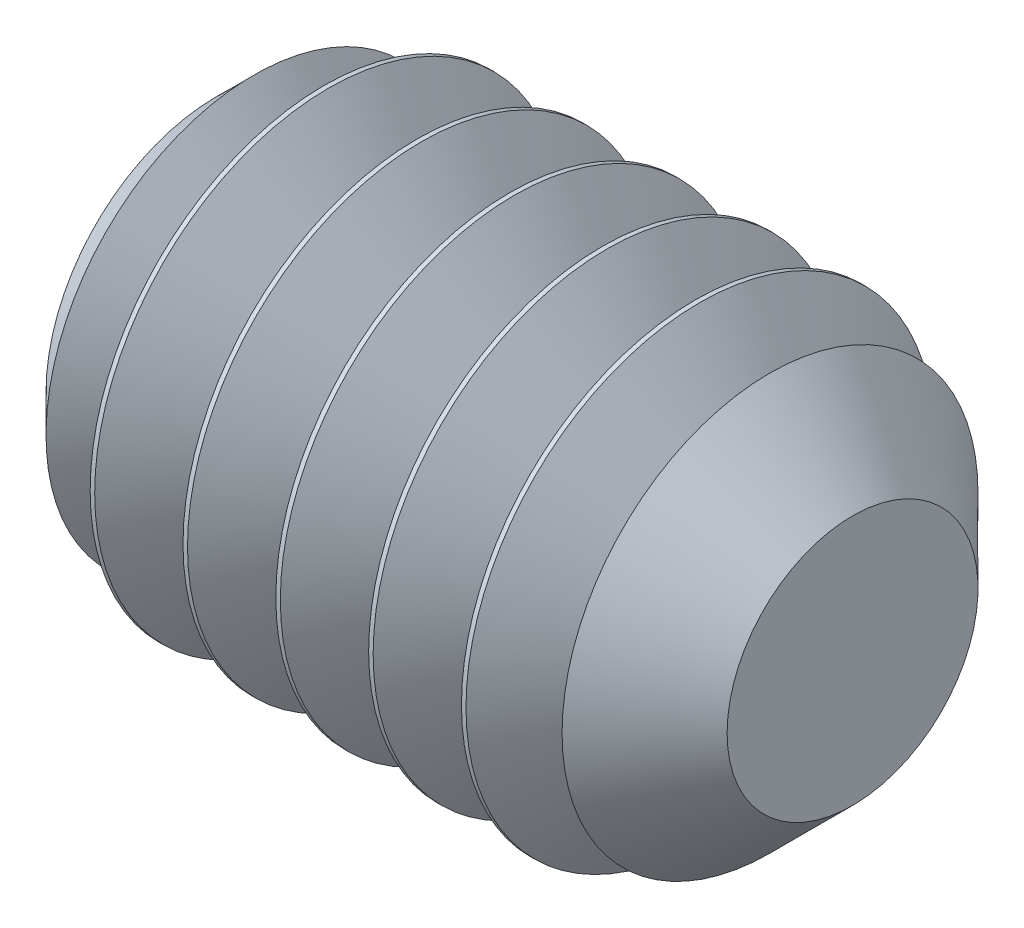
SolidWorks part; units mm, degrees
revolve "BaseBody" add sketch "BodySke" angle 360 about L5
sketch "BodySke" plane through (0, 0, 0) normal (0, 0, 1) x (1, 0, 0)
  line L0 (0, 0) -> (0, 1.2802)
  line L1 (0, 1.2802) -> (0.4724, 1.7526)
  line L2 (0.4724, 1.7526) -> (3.9497, 1.7526)
  line L3 (3.9497, 1.7526) -> (4.7625, 0.9398)
  line L4 (4.7625, 0) -> (0, 0)
  line L5 (-12.7, 0) -> (88.9, 0) construction
  line L6 (4.7625, 0.9398) -> (4.7625, 0)
  line L7 (4.7625, 0.9398) -> (4.7625, 10.4648) construction
  line L8 (0, -1.2802) -> (0.4724, -1.7526) construction
  line L9 (0.7925, 15.875) -> (0.7925, -3.175) construction
  line L10 (3.9497, -1.7526) -> (4.7625, -0.9398) construction
  dimension "Diameter" = 3.5052
  dimension "Drive_ch_ang" = 45
  dimension "Minor_dia" = 2.5603
  dimension "Cup_nose_ang" = 45
  dimension "Cup_dia" = 1.8796
  dimension "Length" = 4.7625
  dimension "Advance" = 0.7925
cosmetic thread "ThreadCosmetic" [suppressed] parameters "Thread_minor"=2.5603
ref_plane "Plane1" through (0, 0, 0) normal (0, 0, 1) x (1, 0, 0)
ref_plane "Plane2" through (0, 0, 0) normal (0, 1, 0) x (1, 0, 0)
ref_plane "Plane3" through (0, 0, 0) normal (1, 0, 0) x (0, 0, -1)
sketch "Sketch2" plane through (0, 0, 0) normal (-1, 0, 0) x (0, 0, 1)
  line L0 (0.4583, 0.7938) -> (-0.4583, 0.7938)
  line L1 (-0.4583, 0.7938) -> (-0.9165, 0)
  line L2 (0.4583, 0.7938) -> (0.9165, 0)
  line L3 (0.4583, -0.7937) -> (0.9165, 0)
  line L4 (0.4583, -0.7937) -> (-0.4583, -0.7937)
  line L5 (-0.4583, -0.7937) -> (-0.9165, 0)
  dimension "Hex_size" = 1.5875
  dimension "D2" = 0.7937
  dimension "D3" = 0.7937
extrude "Hex" cut sketch "Sketch2" against normal blind 2.032
sketch "Sketch4" plane through (0, 4.7709, -0.5249) normal (-1, 0, 0) x (0, 0, 1)
  line L0 (0.5249, -4.7709) -> (1.4647, -4.7709)
  line L1 (0.5249, -4.7709) -> (6.6732, -1.2211) construction
  line L2 (0.5249, -4.7709) -> (0.9948, -3.957)
  line L3 (1.308, -4.5534) -> (1.4211, -4.4881)
  line L4 (1.1048, -4.2014) -> (1.2179, -4.1361)
  arc A0 (1.308, -4.5534) -> (1.1048, -4.2014) centre (0.5249, -4.7709) ccw
  arc A1 (1.4647, -4.7709) -> (1.4211, -4.4881) centre (0.5249, -4.7709) ccw
  arc A2 (0.9948, -3.957) -> (1.2179, -4.1361) centre (0.5249, -4.7709) cw
  circle A3 centre (0.5249, -4.7709) radius 0.8128 construction
  circle A4 centre (0.5249, -4.7709) radius 0.9398 construction
  dimension "Spline_n_dim" = 1.6256
  dimension "Spline_m_dim" = 1.8796
  dimension "D1" = 30
  dimension "Spline_a_dim" = 60
  dimension "Spline_p_dim" = 0.4064
  dimension "D3" = 0.2032
extrude "Spline" [suppressed] cut sketch "Sketch4" against normal blind 1.397
pattern_circular "CirPattern1" [suppressed] count 6 every 60 about axis through (-12.7, 0, 0) along (1, 0, 0)
sketch "ThdSchSke" plane through (0, 0, 0) normal (0, 0, 1) x (1, 0, 0)
  line L0 (0.4724, -1.2802) -> (0.1416, -1.7526)
  line L1 (0.4724, -1.2802) -> (0.8032, -1.7526)
  line L2 (0.8032, -1.7526) -> (0.8032, -2.1907)
  line L3 (-3.175, 0) -> (5.1513, 0) construction
  line L4 (0.4724, 1.7526) -> (0.4724, -1.7526) construction
  line L5 (0.8032, -2.1907) -> (0.1416, -2.1907)
  line L6 (0.1416, -2.1907) -> (0.1416, -1.7526)
  dimension "Thread_minor" = 2.5603
  dimension "Diameter" = 3.5052
revolve "ThreadSchematic" cut sketch "ThdSchSke" angle 360 about L3
pattern_linear "ThdSchPat" count 6 spacing 0.6955 along (1, 0, 0) of "ThreadSchematic"
equation "\"D2@Sketch2\" = \"Hex_size@Sketch2\" / 2"
equation "\"D3@Sketch2\" = \"Hex_size@Sketch2\" / 2"
equation "\"Thread_minor@ThreadCosmetic\" = \"Minor_dia@BodySke\""
equation "\"D1@Sketch4\" = \"Spline_a_dim@Sketch4\" / 2"
equation "\"D3@Sketch4\" = \"Spline_p_dim@Sketch4\" / 2"
equation "\"D2@CirPattern1\" = \"Spline_a_dim@Sketch4\""
equation "\"Num_teeth@CirPattern1\" = 360 / \"D2@CirPattern1\""
equation "\"Thread_minor@ThdSchSke\" = \"Thread_minor@ThreadCosmetic\""
equation "\"Diameter@ThdSchSke\" = \"Diameter@BodySke\""
equation "\"Overcut@ThdSchSke\" = \"Diameter@BodySke\" * 1.25"
equation "\"Num_threads@ThdSchPat\" = int( (\"Length@BodySke\" - ( ( ( \"Diameter@BodySke\" - \"Minor_dia@BodySke\" ) * 0.5 ) / tan( \"Drive_ch_ang@BodySke\" * 0.017453292 ) ) - ( ( ( \"Diameter@BodySke\" - \"Cup_dia@BodySke\" ) * 0.5 ) * tan( \"Cup_nose_ang@BodySke\" * 0.017453292 ) ) ) / \"Advance@BodySke\" + 0.999 )  + 1"
equation "\"Advance@ThdSchPat\" = (\"Length@BodySke\" - ( ( ( \"Diameter@BodySke\" - \"Minor_dia@BodySke\" ) * 0.5 ) / tan( \"Drive_ch_ang@BodySke\" * 0.017453292 ) ) - ( ( ( \"Diameter@BodySke\" - \"Cup_dia@BodySke\" ) * 0.5 ) * tan( \"Cup_nose_ang@BodySke\" * 0.017453292 ) ) ) /  (\"Num_threads@ThdSchPat\" - 1) 'relax it"
equation "' \"Num_threads@ThdSchPat\" = \"Num_threads@ThdSchPat\" - sgn( \"Num_threads@ThdSchPat\" - 1) '---chamfered tips only---"
